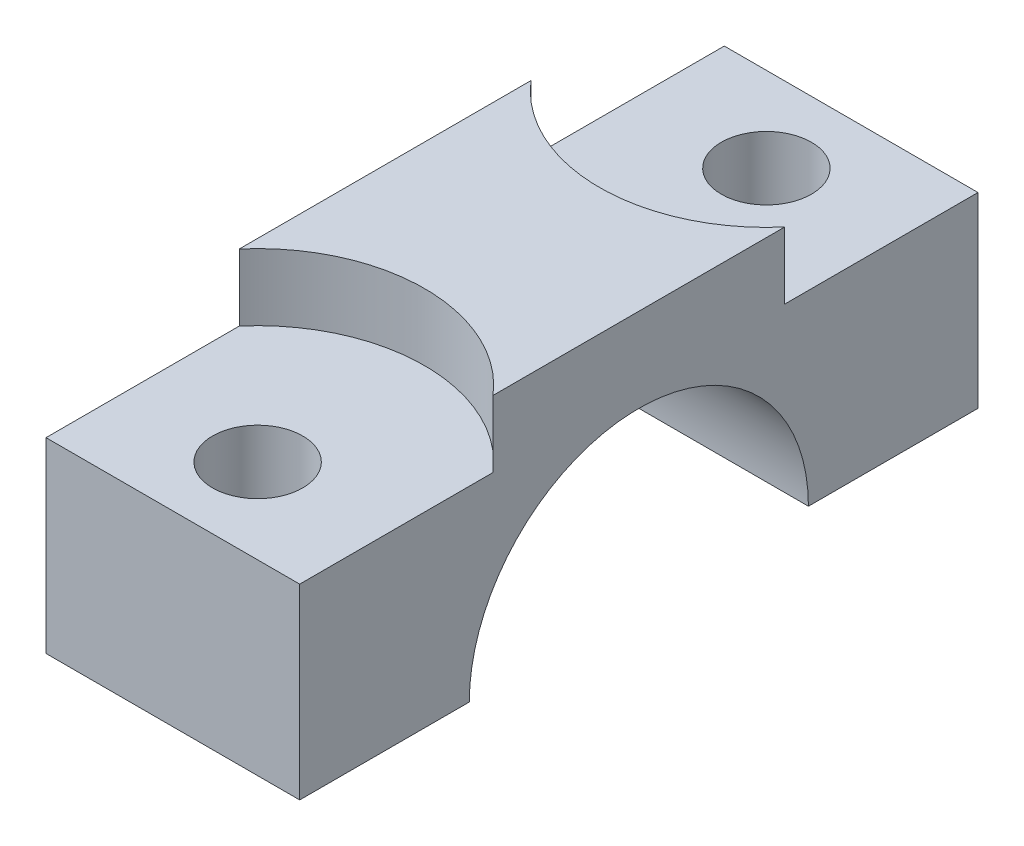
SolidWorks part; units mm, degrees
ref_plane "Front Plane" through (0, 0, 0) normal (0, 0, 1) x (1, 0, 0)
ref_plane "Top Plane" through (0, 0, 0) normal (0, 1, 0) x (1, 0, 0)
ref_plane "Right Plane" through (0, 0, 0) normal (1, 0, 0) x (0, 0, -1)
sketch "Sketch1" plane through (0, 0, 0) normal (1, 0, 0) x (0, 0, -1)
  line L1 (-25.4, 0) -> (25.4, 0)
  line L2 (-25.4, 0) -> (-25.4, 19)
  line L3 (-25.4, 19) -> (25.4, 19)
  line L4 (25.4, 0) -> (25.4, 19)
  circle A0 centre (0, 0) radius 12.7
  dimension "D3" = 25.4
  dimension "D1" = 50.8
  dimension "D2" = 19
extrude "Boss-Extrude1" add sketch "Sketch1" along normal mid plane 19 contours A0 L1 L4 L3 L2
sketch "Sketch4" plane through (0, 0, 0) normal (0, -1, 0) x (1, 0, 0)
  line L0 (0, 25.4) -> (0, 12.7) construction
  line L1 (9.5, 25.4) -> (-9.5, 25.4) construction
  line L2 (9.5, 12.7) -> (-9.5, 12.7) construction
  line L3 (0, -12.7) -> (0, -25.4) construction
  line L4 (9.5, -12.7) -> (-9.5, -12.7) construction
  line L5 (9.5, -25.4) -> (-9.5, -25.4) construction
  point P12 (0, 19.05)
  point P13 (0, -19.05)
hole_wizard "CBORE for M12 Hex Head Cap Screw2" positions "Sketch5" profile "Sketch6" counterbore size "M12" standard "ISO" end condition through all
sketch "Sketch5" plane through (0, 19, 0) normal (0, 1, 0) x (1, 0, 0)
  line L0 (0, 12.7) -> (0, 25.4) construction
  point P0 (0, 19.05)
  point P4 (0, -19.05)
sketch "Sketch6" plane through (0, 19, -19.05) normal (1, 0, 0) x (0, 0, 1)
  line L0 (0, 0) -> (0, 19)
  line L1 (0, 19) -> (3.375, 19)
  line L3 (3.375, 19) -> (3.375, 5)
  line L4 (3.375, 5) -> (12.5, 5)
  line L5 (12.5, 5) -> (12.5, 0)
  line L7 (12.5, 0) -> (0, 0)
  line L11 (0, -6.35) -> (0, 107.95) construction
  dimension "Thru Hole Dia." = 6.75
  dimension "Thru Hole Depth" = 19
  dimension "C'Bore Dia." = 25
  dimension "C'Bore Depth" = 5
